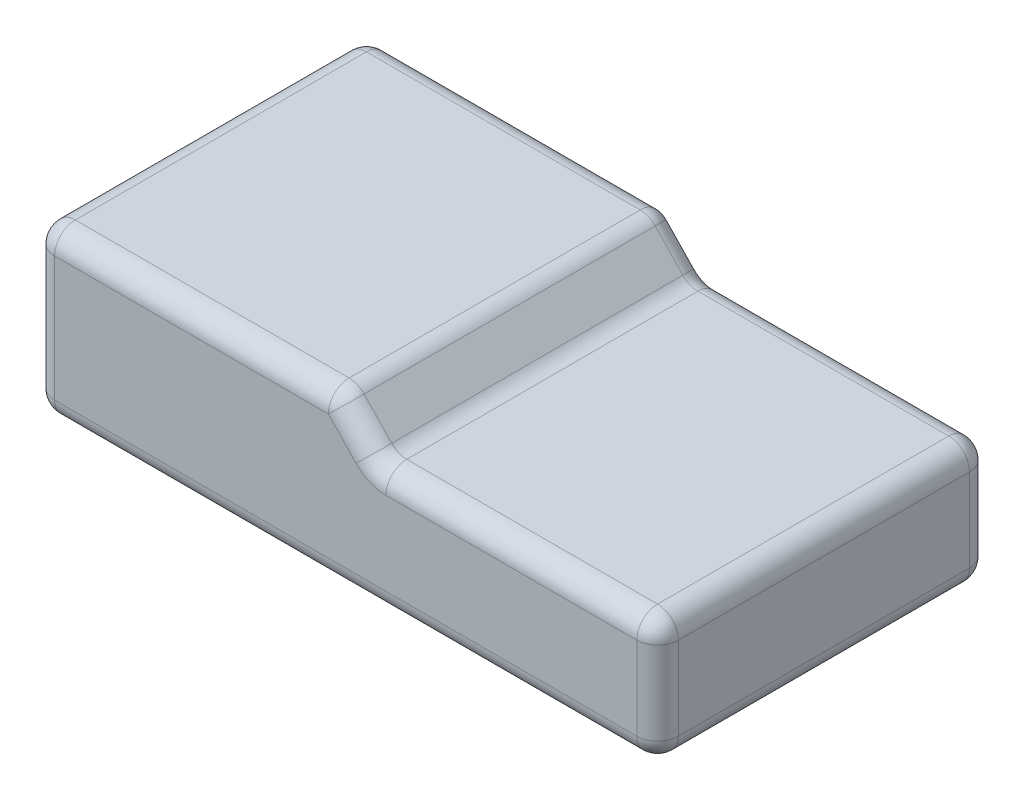
SolidWorks part; units mm, degrees
ref_plane "Front Plane" through (0, 0, 0) normal (0, 0, 1) x (1, 0, 0)
ref_plane "Top Plane" through (0, 0, 0) normal (0, 1, 0) x (1, 0, 0)
ref_plane "Right Plane" through (0, 0, 0) normal (1, 0, 0) x (0, 0, -1)
sketch "Sketch1" plane through (0, 0, 0) normal (0, 0, 1) x (1, 0, 0)
  line L0 (0, 0) -> (0, 10.16)
  line L1 (0, 10.16) -> (18.5311, 10.16)
  line L2 (18.5311, 10.16) -> (20.9681, 7.62)
  line L3 (20.9681, 7.62) -> (38.1, 7.62)
  line L4 (38.1, 7.62) -> (38.1, 0)
  line L5 (38.1, 0) -> (0, 0)
  point P3 (20.9681, 7.62)
  dimension "D1" = 38.1
  dimension "D2" = 10.16
  dimension "D3" = 7.62
extrude "Boss-Extrude1" add sketch "Sketch1" along normal blind 20.32
fillet "Fillet1" radius 1.27 18 edges at (20.9681, 7.62, 10.16) (0, 0, 10.16) (38.1, 0, 10.16) (38.1, 7.62, 10.16) (38.1, 3.81, 0) (29.534, 7.62, 0) (19.7496, 8.89, 0) (0, 5.08, 0) (19.05, 0, 0) (0, 5.08, 20.32) (19.7496, 8.89, 20.32) (29.534, 7.62, 20.32) (38.1, 3.81, 20.32) (19.05, 0, 20.32) (18.5311, 10.16, 10.16) (9.2656, 10.16, 20.32) (0, 10.16, 10.16) (9.2656, 10.16, 0)
